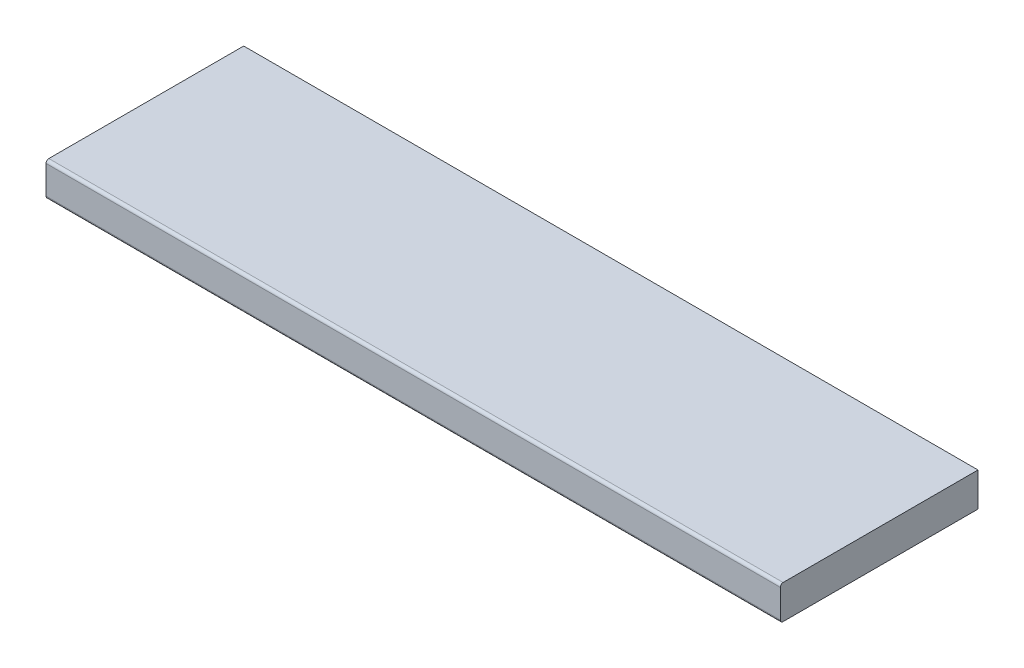
SolidWorks part; units mm, degrees
material "Сосна"
ref_plane "Спереди" through (0, 0, 0) normal (0, 0, 1) x (1, 0, 0)
ref_plane "Сверху" through (0, 0, 0) normal (0, 1, 0) x (1, 0, 0)
ref_plane "Справа" through (0, 0, 0) normal (1, 0, 0) x (0, 0, -1)
sketch "Эскиз1" plane through (0, 0, 0) normal (0, 0, 1) x (1, 0, 0)
  line L1 (-198.9474, 28.7368) -> (1101.0526, 28.7368)
  line L2 (-198.9474, 28.7368) -> (-198.9474, -31.2632)
  line L3 (-198.9474, -31.2632) -> (1101.0526, -31.2632)
  line L4 (1101.0526, 28.7368) -> (1101.0526, -31.2632)
  dimension "D1" = 60
  dimension "D2" = 1300
extrude "Подоконник малого окна" add sketch "Эскиз1" along normal blind 350
fillet "Скругление2" radius 5 2 edges at (451.0526, -31.2632, 350) (451.0526, 28.7368, 350)
